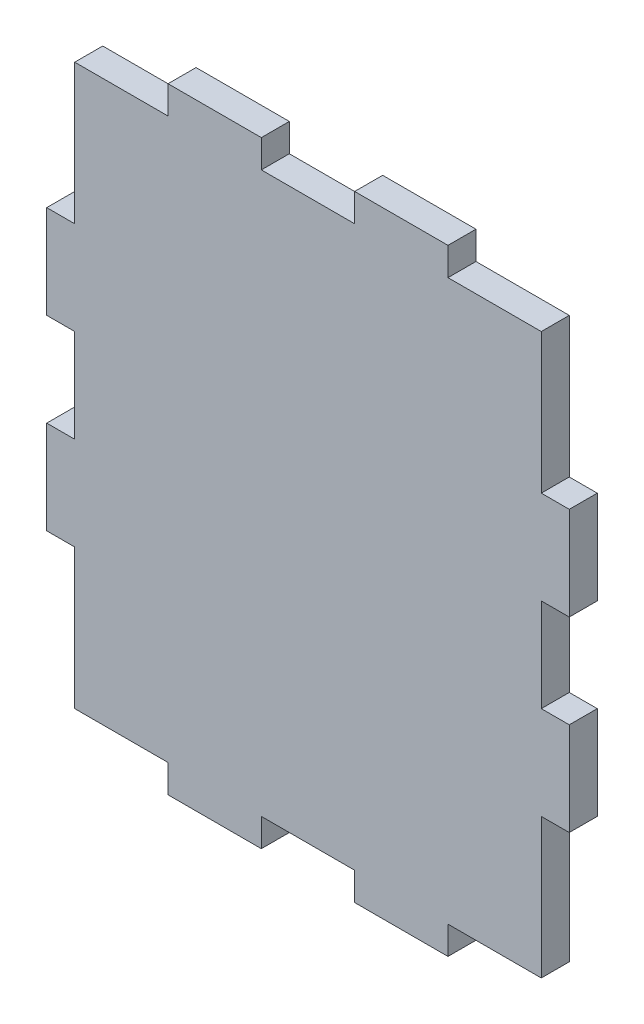
SolidWorks part; units mm, degrees
ref_plane "Plano frontal" through (0, 0, 0) normal (0, 0, 1) x (1, 0, 0)
ref_plane "Plano superior" through (0, 0, 0) normal (0, 1, 0) x (1, 0, 0)
ref_plane "Plano direito" through (0, 0, 0) normal (1, 0, 0) x (0, 0, -1)
sketch "Esboço1" plane through (0, 0, 0) normal (0, 0, 1) x (1, 0, 0)
  line L0 (-40, 0) -> (-20, 0)
  line L1 (-20, 0) -> (-20, 6)
  line L2 (-20, 6) -> (0, 6)
  line L3 (0, 6) -> (0, 0)
  line L4 (0, 0) -> (20, 0)
  line L5 (20, 0) -> (20, 6)
  line L6 (20, 6) -> (40, 6)
  line L7 (40, 6) -> (40, 0)
  line L8 (40, 0) -> (60, 0)
  line L9 (60, 0) -> (60, -30)
  line L10 (60, -30) -> (66, -30)
  line L11 (66, -30) -> (66, -50)
  line L12 (66, -50) -> (60, -50)
  line L13 (60, -50) -> (60, -70)
  line L14 (60, -70) -> (66, -70)
  line L15 (66, -70) -> (66, -90)
  line L16 (66, -90) -> (60, -90)
  line L17 (60, -90) -> (60, -120)
  line L18 (60, -120) -> (40, -120)
  line L19 (40, -120) -> (40, -126)
  line L20 (40, -126) -> (20, -126)
  line L21 (20, -126) -> (20, -120)
  line L22 (20, -120) -> (0, -120)
  line L23 (0, -120) -> (0, -126)
  line L24 (0, -126) -> (-20, -126)
  line L25 (-20, -126) -> (-20, -120)
  line L26 (-20, -120) -> (-40, -120)
  line L27 (-40, -120) -> (-40, -90)
  line L28 (-40, -90) -> (-46, -90)
  line L29 (-46, -90) -> (-46, -70)
  line L30 (-46, -70) -> (-40, -70)
  line L31 (-40, -70) -> (-40, -50)
  line L32 (-40, -50) -> (-46, -50)
  line L33 (-46, -50) -> (-46, -30)
  line L34 (-46, -30) -> (-40, -30)
  line L35 (-40, -30) -> (-40, 0)
  line L36 (10, 0) -> (10, -120) construction
  line L37 (-40, -60) -> (60, -60) construction
  dimension "D1" = 6
  dimension "D2" = 6
  dimension "D3" = 100
  dimension "D4" = 20
  dimension "D5" = 20
  dimension "D6" = 30
  dimension "D7" = 20
  dimension "D8" = 30
  dimension "D9" = 6
  dimension "D10" = 6
  dimension "D11" = 6
  dimension "D12" = 6
  dimension "D13" = 120
  dimension "D14" = 20
extrude "Ressalto-extrusão1" add sketch "Esboço1" along normal blind 6
